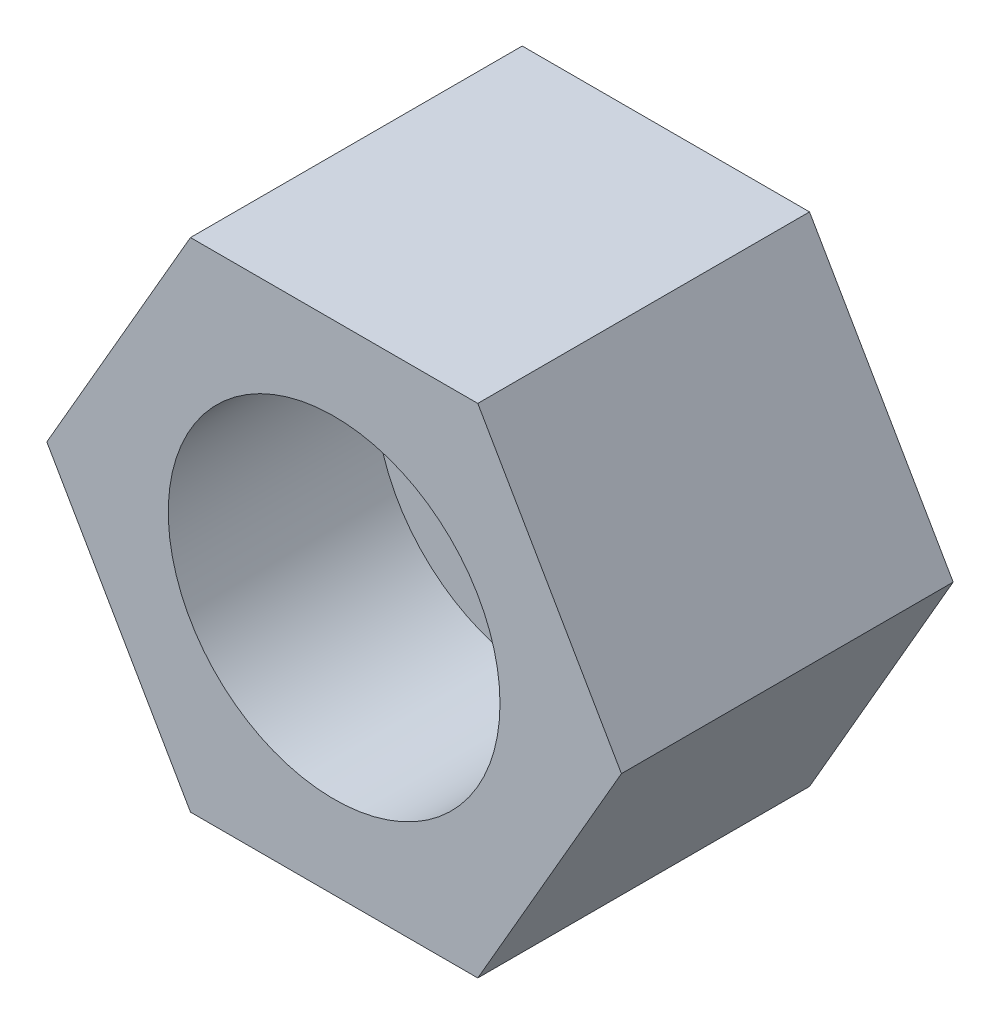
SolidWorks part; units mm, degrees
material "Brass"
ref_plane "Front Plane" through (0, 0, 0) normal (0, 0, 1) x (1, 0, 0)
ref_plane "Top Plane" through (0, 0, 0) normal (0, 1, 0) x (1, 0, 0)
ref_plane "Right Plane" through (0, 0, 0) normal (1, 0, 0) x (0, 0, -1)
sketch "Sketch1" plane through (0, 0, 0) normal (0, 0, 1) x (1, 0, 0)
  line L1 (6.9282, 0) -> (3.4641, 6)
  line L2 (3.4641, 6) -> (-3.4641, 6)
  line L3 (-3.4641, 6) -> (-6.9282, 0)
  line L4 (-6.9282, 0) -> (-3.4641, -6)
  line L5 (-3.4641, -6) -> (3.4641, -6)
  line L6 (3.4641, -6) -> (6.9282, 0)
  circle A0 centre (0, 0) radius 6 construction
  circle A1 centre (0, 0) radius 2
  dimension "D2" = 4
  dimension "D1" = 12
extrude "Boss-Extrude1" add sketch "Sketch1" along normal mid plane 8
sketch "Sketch2" plane through (0, 0, 4) normal (0, 0, 1) x (1, 0, 0)
  circle A0 centre (0, 0) radius 4
  dimension "D1" = 8
extrude "Cut-Extrude1" cut sketch "Sketch2" against normal blind 5
cosmetic thread "Cosmetic Thread1" parameters "D2"=10
